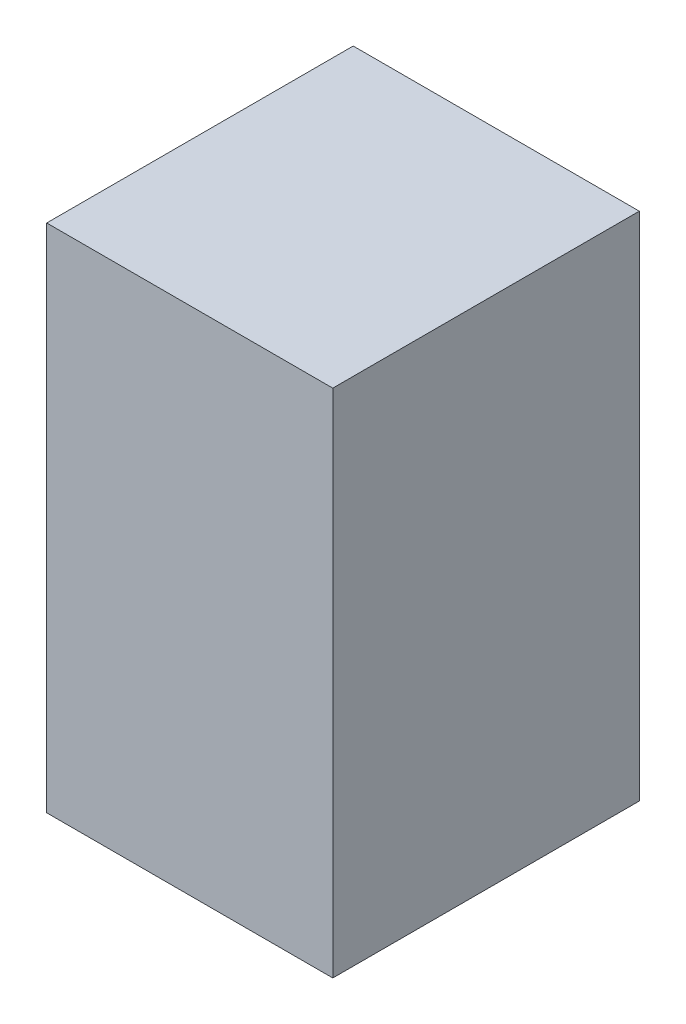
SolidWorks part; units mm, degrees
ref_plane "Front Plane" through (0, 0, 0) normal (0, 0, 1) x (1, 0, 0)
ref_plane "Top Plane" through (0, 0, 0) normal (0, 1, 0) x (1, 0, 0)
ref_plane "Right Plane" through (0, 0, 0) normal (1, 0, 0) x (0, 0, -1)
other "Configuration Table"
sketch "Sketch1" plane through (0, 0, 0) normal (0, 0, 1) x (1, 0, 0)
  line L1 (714, 1540) -> (728, 1540)
  line L2 (714, 1540) -> (714, 1565)
  line L3 (714, 1565) -> (728, 1565)
  line L4 (728, 1540) -> (728, 1565)
extrude "DET2_gergi_makarasi_braketi_1" add sketch "Sketch1" against normal blind 15 from offset 55 separate body
